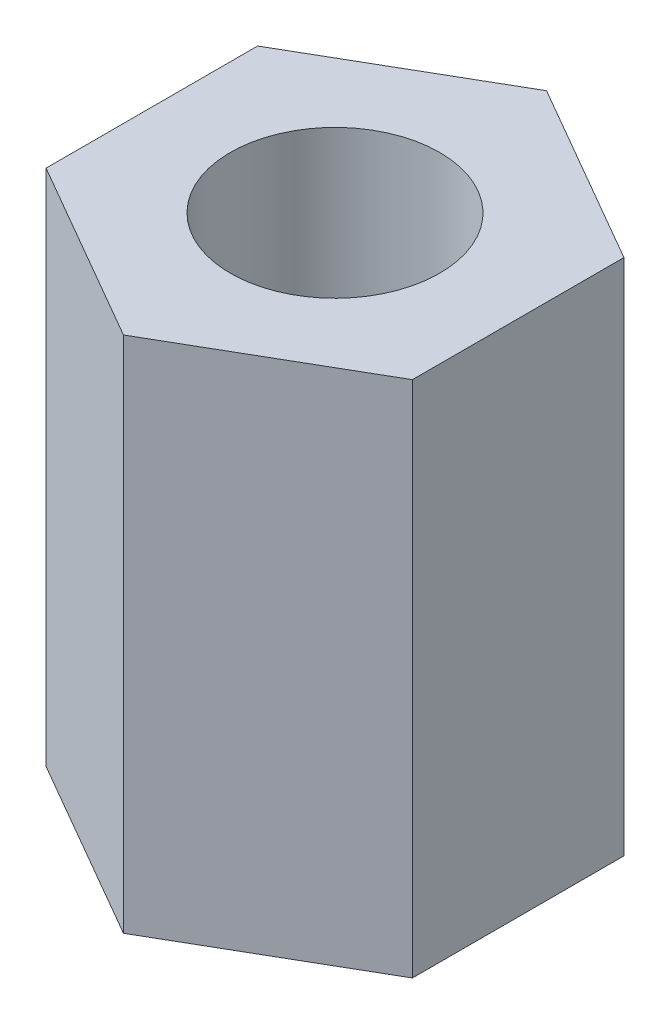
SolidWorks part; units mm, degrees
ref_plane "Front Plane" through (0, 0, 0) normal (0, 0, 1) x (1, 0, 0)
ref_plane "Top Plane" through (0, 0, 0) normal (0, 1, 0) x (1, 0, 0)
ref_plane "Right Plane" through (0, 0, 0) normal (1, 0, 0) x (0, 0, -1)
sketch "Sketch1" plane through (0, 0, 0) normal (0, 1, 0) x (1, 0, 0)
  line L1 (-3.5, -2.0207) -> (0, -4.0415)
  line L2 (0, -4.0415) -> (3.5, -2.0207)
  line L3 (3.5, -2.0207) -> (3.5, 2.0207)
  line L4 (3.5, 2.0207) -> (0, 4.0415)
  line L5 (0, 4.0415) -> (-3.5, 2.0207)
  line L6 (-3.5, 2.0207) -> (-3.5, -2.0207)
  circle A0 centre (0, 0) radius 3.5 construction
  circle A1 centre (0, 0) radius 2
  dimension "D1" = 4
  dimension "D2" = 7
extrude "Boss-Extrude1" add sketch "Sketch1" along normal blind 9.9
